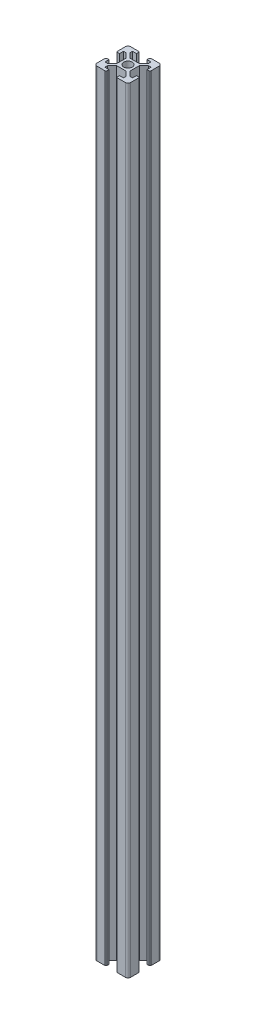
SolidWorks part; units mm, degrees
material "1060 合金"
ref_plane "前视" through (0, 0, 0) normal (0, 0, 1) x (1, 0, 0)
ref_plane "上视" through (0, 0, 0) normal (0, 1, 0) x (1, 0, 0)
ref_plane "右视" through (0, 0, 0) normal (1, 0, 0) x (0, 0, -1)
sketch "草图1" plane through (0, 0, 0) normal (0, 1, 0) x (1, 0, 0)
  line L0 (13.9, 12.8393) -> (13.9, 7.1607)
  line L5 (12.8393, 6.1) -> (7.1607, 6.1)
  line L6 (0, 20) -> (20, 0) construction
  line L7 (20, 20) -> (0, 0) construction
  line L8 (4.5, 18.2) -> (6.9, 18.2)
  line L9 (18.2, 4.5) -> (18.2, 6.9)
  line L10 (4.5, 1.8) -> (6.9, 1.8)
  line L11 (1.8, 4.5) -> (1.8, 6.9)
  line L12 (3.4393, 15.5) -> (6.1, 12.8393)
  line L16 (1.5, 0) -> (6.4, 0)
  line L17 (4.5, 16.5607) -> (7.1607, 13.9)
  line L18 (15.5, 16.5607) -> (12.8393, 13.9)
  line L19 (16.5607, 15.5) -> (13.9, 12.8393)
  line L21 (0, 13.6) -> (0.5, 13.1)
  line L22 (19.4697, 20.5303) -> (-0.5303, 0.5303) construction
  line L23 (20.5303, 19.4697) -> (0.5303, -0.5303) construction
  line L24 (13.9, 7.1607) -> (16.5607, 4.5)
  line L25 (12.8393, 6.1) -> (15.5, 3.4393)
  line L28 (7.1607, 6.1) -> (4.5, 3.4393)
  line L30 (6.1, 7.1607) -> (3.4393, 4.5)
  line L31 (0.5, 6.9) -> (1.8, 6.9)
  line L32 (0.5, 13.1) -> (1.8, 13.1)
  line L33 (6.9, 19.5) -> (6.9, 18.2)
  line L34 (13.1, 19.5) -> (13.1, 18.2)
  line L35 (6.9, 1.8) -> (6.9, 0.5)
  line L36 (6.1, 7.1607) -> (6.1, 12.8393)
  line L37 (13.1, 1.8) -> (13.1, 0.5)
  line L38 (7.1607, 13.9) -> (12.8393, 13.9)
  line L39 (1.8, 13.1) -> (1.8, 15.5)
  line L40 (0, 1.5) -> (0, 6.4)
  line L41 (18.2, 13.1) -> (19.5, 13.1)
  line L42 (1.8, 4.5) -> (3.4393, 4.5)
  line L44 (18.2, 6.9) -> (19.5, 6.9)
  line L46 (13.1, 1.8) -> (15.5, 1.8)
  line L51 (13.1, 18.2) -> (15.5, 18.2)
  line L54 (18.2, 13.1) -> (18.2, 15.5)
  line L56 (4.5, 1.8) -> (4.5, 3.4393)
  line L57 (1.5, 20) -> (6.4, 20)
  line L58 (0, 18.5) -> (0, 13.6)
  line L59 (1.8, 15.5) -> (3.4393, 15.5)
  line L60 (4.5, 18.2) -> (4.5, 16.5607)
  line L61 (18.5, 20) -> (13.6, 20)
  line L62 (20, 18.5) -> (20, 13.6)
  line L63 (18.2, 15.5) -> (16.5607, 15.5)
  line L64 (15.5, 18.2) -> (15.5, 16.5607)
  line L65 (18.5, 0) -> (13.6, 0)
  line L66 (20, 1.5) -> (20, 6.4)
  line L67 (18.2, 4.5) -> (16.5607, 4.5)
  line L68 (15.5, 1.8) -> (15.5, 3.4393)
  line L69 (0, 6.4) -> (0.5, 6.9)
  line L70 (6.4, 0) -> (6.9, 0.5)
  line L72 (13.6, 0) -> (13.1, 0.5)
  line L73 (20, 6.4) -> (19.5, 6.9)
  line L75 (20, 13.6) -> (19.5, 13.1)
  line L76 (13.6, 20) -> (13.1, 19.5)
  line L77 (6.4, 20) -> (6.9, 19.5)
  circle A0 centre (10, 10) radius 2.55
  arc A1 (18.5, 20) -> (20, 18.5) centre (18.5, 18.5) cw
  arc A2 (0, 18.5) -> (1.5, 20) centre (1.5, 18.5) cw
  arc A3 (0, 1.5) -> (1.5, 0) centre (1.5, 1.5) ccw
  arc A4 (20, 1.5) -> (18.5, 0) centre (18.5, 1.5) cw
  dimension "D3" = 5.1
  dimension "D5" = 1.5
  dimension "D6" = 1.5
  dimension "D7" = 1.5
  dimension "D8" = 1.5
  dimension "D1" = 20
  dimension "D2" = 20
extrude "凸台-拉伸2" add sketch "草图1" along normal blind 460 contours L51 L64 L18 L38 L17 L60 L8 L33 L77 L57 A2 L58 L21 L32 L39 L59 L12 L36 L30 L42 L11 L31 L69 L40 A3 L16 L70 L35 L10 L56 L28 L5 L25 L68 L46 L37 L72 L65 A4 L66 L73 L44 L9 L67 L24 L0 L19 L63 L54 L41 L75 L62 A1 L61 L76 L34
sketch "草图4" plane through (0, 0, 0) normal (0, -1, 0) x (1, 0, 0)
  circle A4 centre (10, -10) radius 2.55
  dimension "D1" = 5.1
extrude "切除-拉伸2" cut sketch "草图4" against normal through all
